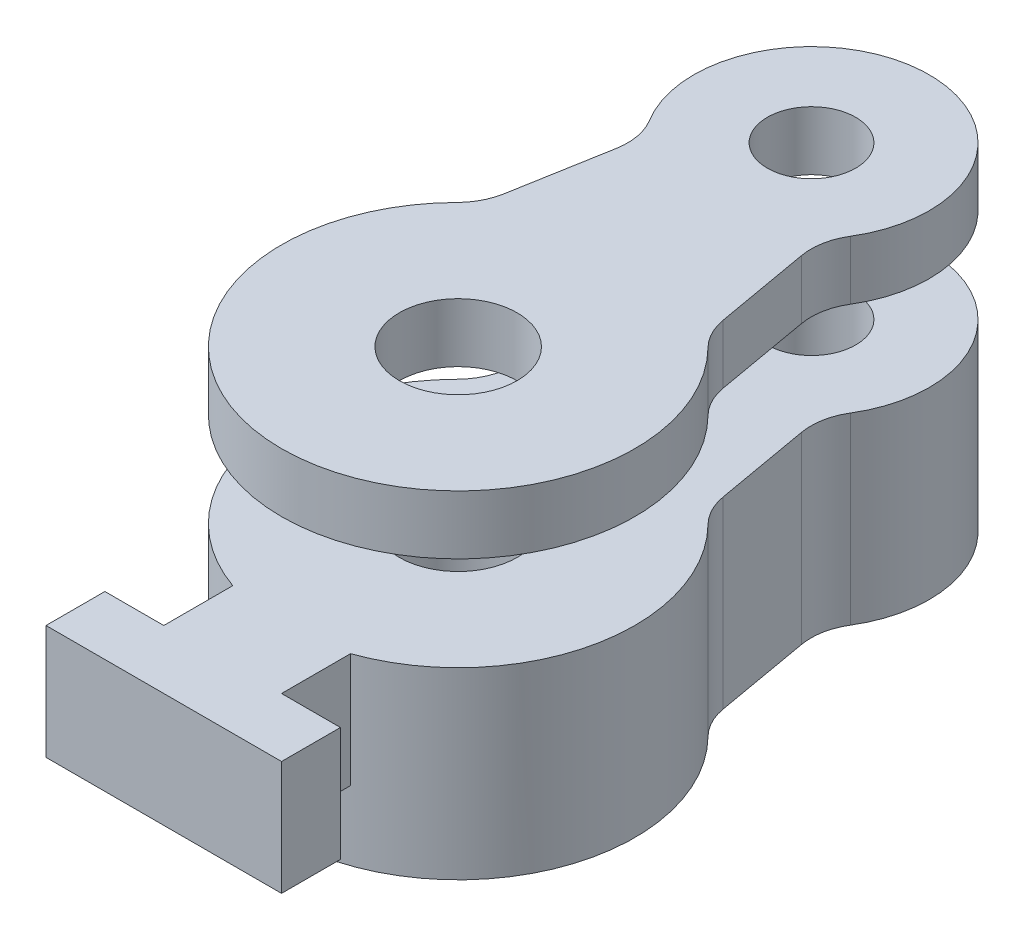
SolidWorks part; units mm, degrees
ref_plane "Front Plane" through (0, 0, 0) normal (0, 0, 1) x (1, 0, 0)
ref_plane "Top Plane" through (0, 0, 0) normal (0, 1, 0) x (1, 0, 0)
ref_plane "Right Plane" through (0, 0, 0) normal (1, 0, 0) x (0, 0, -1)
sketch "Sketch1" plane through (0, 0, 0) normal (0, 1, 0) x (1, 0, 0)
  line L0 (0, 0) -> (0, 76.2) construction
  line L5 (-24.3579, 29.2968) -> (-19.05, 59.3995)
  line L6 (24.3579, 29.2968) -> (19.05, 59.3995)
  arc A0 (-24.3579, 29.2968) -> (24.3579, 29.2968) centre (0, 0) ccw
  circle A1 centre (0, 0) radius 12.7
  arc A2 (19.05, 59.3995) -> (-19.05, 59.3995) centre (0, 76.2) ccw
  circle A3 centre (0, 76.2) radius 9.525
  dimension "D1" = 25.4
  dimension "D2" = 38.1
  dimension "D6" = 19.05
  dimension "D7" = 25.4
  dimension "D3" = 10
  dimension "D4" = 38.1
  dimension "D5" = 76.2
extrude "Boss-Extrude1" add sketch "Sketch1" along normal blind 12.7
fillet "Fillet1" radius 12.7 4 edges at (19.05, 6.35, -59.3995) (-24.3579, 6.35, -29.2968) (-19.05, 6.35, -59.3995) (24.3579, 6.35, -29.2968)
sketch "Sketch2" plane through (0, 12.7, 0) normal (0, 1, 0) x (1, 0, 0)
  line L0 (12.7, -35.921) -> (12.7, -50.8)
  line L1 (12.7, -50.8) -> (25.4, -50.8)
  line L2 (25.4, -50.8) -> (25.4, -63.5)
  line L3 (25.4, -63.5) -> (-25.4, -63.5)
  line L4 (0, 0) -> (0, -63.5) construction
  line L5 (-25.4, -50.8) -> (-25.4, -63.5)
  line L6 (-12.7, -50.8) -> (-25.4, -50.8)
  line L7 (-12.7, -35.921) -> (-12.7, -50.8)
  arc A0 (-27.091, 26.7897) -> (27.091, 26.7897) centre (0, 0) ccw construction
  arc A1 (-12.7, -35.921) -> (12.7, -35.921) centre (0, 0) ccw
  dimension "D1" = 12.7
  dimension "D2" = 63.5
  dimension "D3" = 25.4
  dimension "D4" = 12.7
ref_plane "Plane1" through (0, -20.32, 0) normal (0, 1, 0) x (1, 0, 0)
sketch "Sketch3" plane through (0, -20.32, 0) normal (0, 1, 0) x (1, 0, 0)
  line L2 (23.6143, 33.5143) -> (19.9848, 54.0978)
  line L3 (-19.9848, 54.0978) -> (-23.6143, 33.5143)
  line L4 (23.6143, 33.5143) -> (19.9848, 54.0978)
  line L5 (-19.9848, 54.0978) -> (-23.6143, 33.5143)
  circle A1 centre (0, 76.2) radius 9.525
  circle A2 centre (0, 76.2) radius 9.525
  circle A3 centre (0, 0) radius 12.7
  circle A4 centre (0, 0) radius 12.7
  arc A6 (21.6613, 62.9354) -> (-21.6613, 62.9354) centre (0, 76.2) ccw
  arc A7 (21.6613, 62.9354) -> (19.9848, 54.0978) centre (32.4919, 56.3031) ccw
  arc A8 (23.6143, 33.5143) -> (27.091, 26.7897) centre (36.1213, 35.7196) ccw
  arc A9 (-27.091, 26.7897) -> (27.091, 26.7897) centre (0, 0) ccw
  arc A10 (-27.091, 26.7897) -> (-23.6143, 33.5143) centre (-36.1213, 35.7196) ccw
  arc A11 (-19.9848, 54.0978) -> (-21.6613, 62.9354) centre (-32.4919, 56.3031) ccw
  arc A12 (21.6613, 62.9354) -> (-21.6613, 62.9354) centre (0, 76.2) ccw
  arc A13 (21.6613, 62.9354) -> (19.9848, 54.0978) centre (32.4919, 56.3031) ccw
  arc A14 (23.6143, 33.5143) -> (27.091, 26.7897) centre (36.1213, 35.7196) ccw
  arc A15 (-27.091, 26.7897) -> (27.091, 26.7897) centre (0, 0) ccw
  arc A16 (-27.091, 26.7897) -> (-23.6143, 33.5143) centre (-36.1213, 35.7196) ccw
  arc A17 (-19.9848, 54.0978) -> (-21.6613, 62.9354) centre (-32.4919, 56.3031) ccw
  dimension "D1" = 0
  dimension "D2" = 0
  dimension "D3" = 0
extrude "Boss-Extrude2" add sketch "Sketch3" against normal blind 39.624 separate body
sketch "Sketch4" plane through (0, -20.32, 0) normal (0, 1, 0) x (1, 0, 0)
  line L7 (12.7, -50.8) -> (12.7, -35.921)
  line L8 (25.4, -50.8) -> (12.7, -50.8)
  line L9 (25.4, -63.5) -> (25.4, -50.8)
  line L10 (-25.4, -63.5) -> (25.4, -63.5)
  line L11 (-25.4, -50.8) -> (-25.4, -63.5)
  line L12 (-12.7, -50.8) -> (-25.4, -50.8)
  line L13 (-12.7, -35.921) -> (-12.7, -50.8)
  line L14 (12.7, -50.8) -> (12.7, -35.921)
  line L15 (25.4, -50.8) -> (12.7, -50.8)
  line L16 (25.4, -63.5) -> (25.4, -50.8)
  line L17 (-25.4, -63.5) -> (25.4, -63.5)
  line L18 (-25.4, -50.8) -> (-25.4, -63.5)
  line L19 (-12.7, -50.8) -> (-25.4, -50.8)
  line L20 (-12.7, -35.921) -> (-12.7, -50.8)
  arc A1 (-12.7, -35.921) -> (12.7, -35.921) centre (0, 0) ccw
  arc A2 (-12.7, -35.921) -> (12.7, -35.921) centre (0, 0) ccw
  dimension "D1" = 0
extrude "Boss-Extrude3" add sketch "Sketch4" against normal blind 24.638
